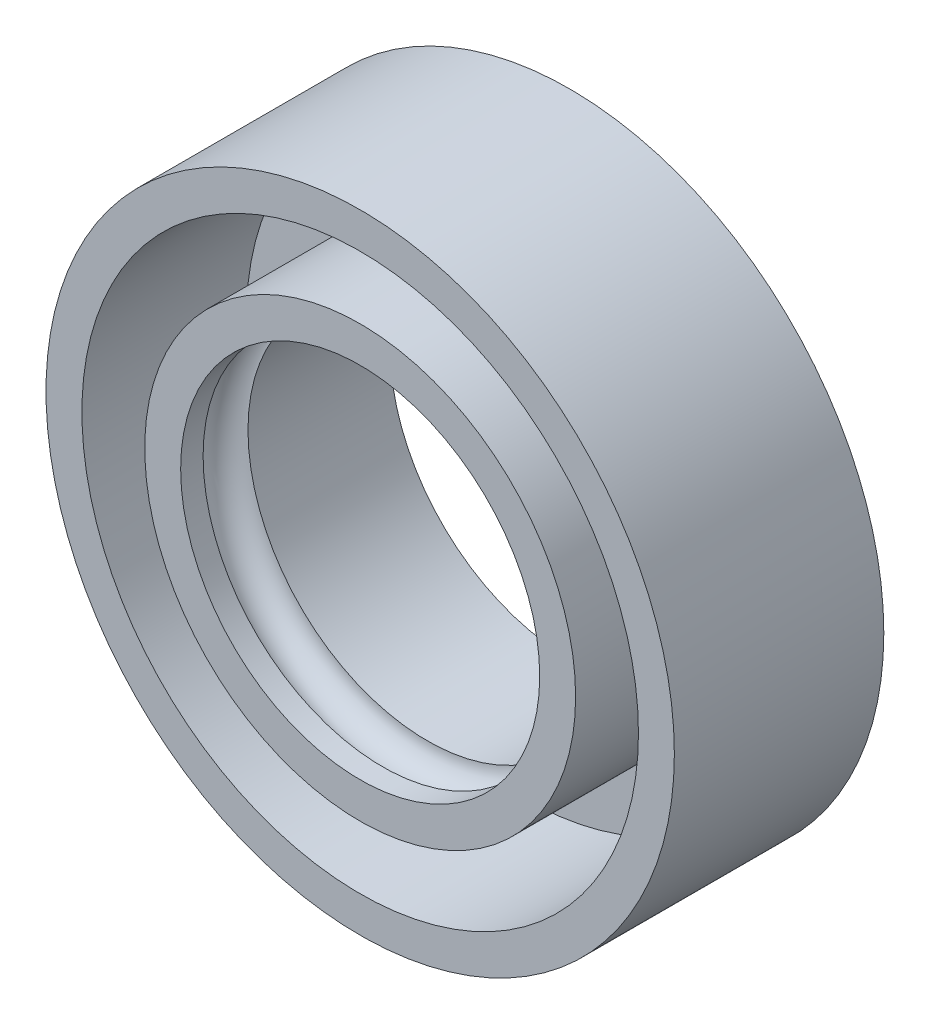
SolidWorks part; units mm, degrees
ref_plane "前视基准面" through (0, 0, 0) normal (0, 0, 1) x (1, 0, 0)
ref_plane "上视基准面" through (0, 0, 0) normal (0, 1, 0) x (1, 0, 0)
ref_plane "右视基准面" through (0, 0, 0) normal (1, 0, 0) x (0, 0, -1)
sketch "草图1" plane through (0, 0, 0) normal (0, 0, 1) x (1, 0, 0)
  circle A0 centre (0, 0) radius 10.5
  dimension "D1" = 21
extrude "凸台-拉伸1" add sketch "草图1" along normal blind 7
sketch "草图2" plane through (0, 0, 7) normal (0, 0, 1) x (1, 0, 0)
  circle A0 centre (0, 0) radius 6
  dimension "D1" = 12
extrude "切除-拉伸1" cut sketch "草图2" against normal through all
sketch "草图3" plane through (0, 0, 7) normal (0, 0, 1) x (1, 0, 0)
  circle A2 centre (0, 0) radius 9.3
  circle A3 centre (0, 0) radius 9.3
  circle A5 centre (0, 0) radius 7.2
  circle A6 centre (0, 0) radius 7.2
  dimension "D1" = 1.2
  dimension "D2" = 1.2
extrude "切除-拉伸2" cut sketch "草图3" against normal blind 5.5
ref_plane "基准面1" through (0, 0, 5.5) normal (0, 0, 1) x (1, 0, 0)
sketch "草图5" plane through (0, 0, 5.5) normal (0, 0, 1) x (1, 0, 0)
  circle A0 centre (0, 0) radius 6
  circle A17 centre (0, 0) radius 7.2 construction
  dimension "D1" = 1.2
sweep "切除-扫描1" cut path "草图5" circular profile diameter 1.5 parameters "D3"=1.5
